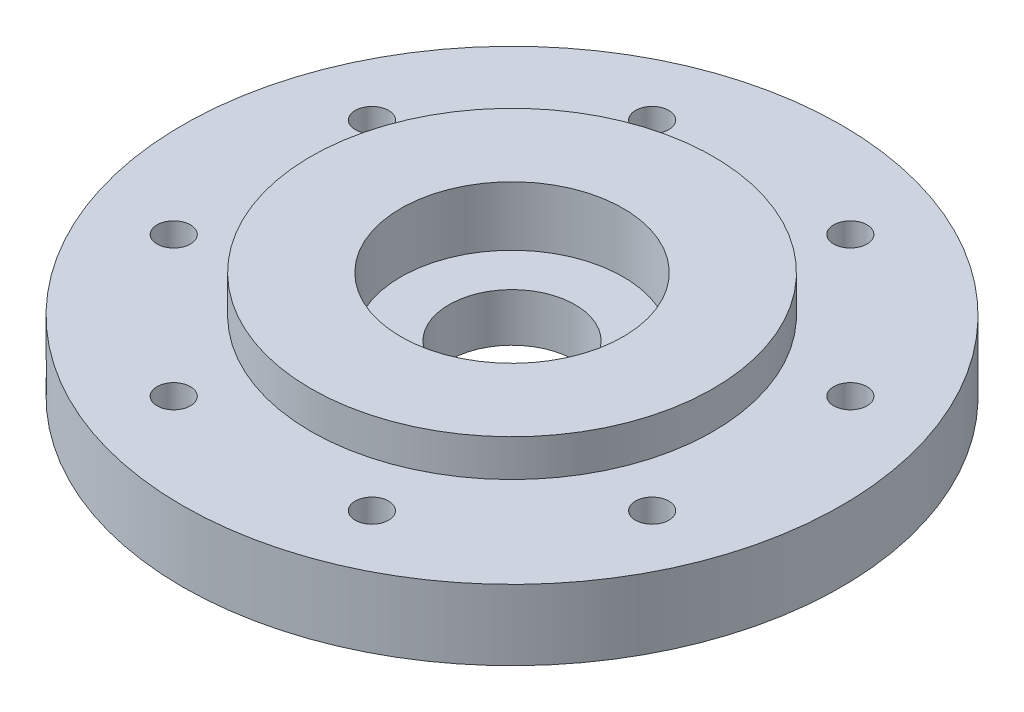
SolidWorks part; units mm, degrees
material "1060 Alloy"
ref_plane "Front" through (0, 0, 0) normal (0, 0, 1) x (1, 0, 0)
ref_plane "Top" through (0, 0, 0) normal (0, 1, 0) x (1, 0, 0)
ref_plane "Right" through (0, 0, 0) normal (1, 0, 0) x (0, 0, -1)
sketch "Sketch1" plane through (0, 0, 0) normal (0, 1, 0) x (1, 0, 0)
  circle A4 centre (0, 0) radius 8.5
  circle A5 centre (0, 0) radius 44.45
  point P0 (0, 0)
  point P17 (0, 0)
  dimension "D6" = 17
  dimension "D1" = 88.9
extrude "body and center hole" add sketch "Sketch1" along normal blind 14.5
sketch "Sketch5" plane through (0, 14.5, 0) normal (0, 1, 0) x (1, 0, 0)
  circle A0 centre (0, 0) radius 15
  dimension "D1" = 30
extrude "big seal cut" cut sketch "Sketch5" against normal blind 8
sketch "Sketch6" plane through (0, 14.5, 0) normal (0, 1, 0) x (1, 0, 0)
  line L0 (0, 0) -> (0, 44.45) construction
  line L1 (0, 0) -> (17.0103, 41.0664) construction
  circle A0 centre (0, 0) radius 44.45 construction
  circle A1 centre (13.3652, 32.2665) radius 2.25
  dimension "D2" = 4.5
  dimension "D1" = 22.5
  dimension "D3" = 34.925
extrude "impeller housing bolt holes" cut sketch "Sketch6" against normal blind 38
pattern_circular "impeller housing bolt pattern" count 8 over 360 about axis through (0, 0, 0) along (0, 1, 0) of "impeller housing bolt holes"
sketch "Sketch7" plane through (0, 14.5, 0) normal (0, 1, 0) x (1, 0, 0)
  circle A0 centre (0, 0) radius 27.1319
  circle A1 centre (0, 0) radius 44.45
  circle A3 centre (0, 0) radius 44.45 construction
  dimension "D1" = 54.2638
extrude "impeller recess" cut sketch "Sketch7" against normal blind 5
sketch "Sketch8" plane through (0, 0, 0) normal (0, -1, 0) x (-1, 0, 0)
  line L0 (0, 0) -> (0, 44.45) construction
  circle A0 centre (0, 0) radius 25.4 construction
  circle A1 centre (0, -25.4) radius 3
  circle A2 centre (0, 0) radius 44.45 construction
  dimension "D1" = 50.8
  dimension "D2" = 6
extrude "bolt hole" cut sketch "Sketch8" against normal blind 7.5 contours A1
pattern_circular "big bolt pattern" count 4 over 360 about axis through (0, 0, 0) along (0, 1, 0) of "bolt hole"
ref_plane "pressure tap orientation" through (-10.5787, 0, 10.5787) normal (-0.7071, 0, 0.7071) x (0.7071, 0, 0.7071)
sketch "Sketch9" plane through (-10.5787, 0, 10.5787) normal (-0.7071, 0, 0.7071) x (0.7071, 0, 0.7071)
  line L0 (0, 6.5) -> (0, 0) construction
  line L1 (15, 6.5) -> (-15, 6.5) construction
  circle A0 centre (0, 3.25) radius 1
  dimension "D1" = 2
extrude "pressure hole" cut sketch "Sketch9" against normal blind 10 and the other way blind 50
sketch "pressure tap end position" plane through (0, 0, 0) normal (0, 1, 0) x (1, 0, 0)
  line L0 (0, 0) -> (-31.4309, -31.4309) construction
  line L1 (-6.6758, -5.2616) -> (-32.13, -30.7158) construction
  circle A0 centre (0, 0) radius 44.45 construction
ref_plane "pressure tap face plane" through (-31.4309, 0, 31.4309) normal (-0.7071, 0, 0.7071) x (0.7071, 0, 0.7071)
sketch "Sketch12" plane through (-31.4309, 0, 31.4309) normal (-0.7071, 0, 0.7071) x (0.7071, 0, 0.7071)
  circle A0 centre (0, 3.25) radius 2.5
  dimension "D1" = 5
extrude "pressure tap fitting bore" cut sketch "Sketch12" against normal blind 8
equation "\"D6@Sketch1\"=\"impeller boss diameter\"+2mm"
equation "\"D1@body and center hole\"=\"big seal plate thickness\""
equation "\"bearing OD\" = 30mm"
equation "\"bearing outer race thickness\"= 1mm"
equation "\"bearing ID\"= 10mm"
equation "\"bearing depth\"= 9mm"
equation "\"bearing inner race thickness\"= 1mm"
equation "\"small seal OD\" = 20mm"
equation "\"small seal ID\"= 8mm"
equation "\"small seal depth\" = 6mm"
equation "\"big seal OD\" = 30mm"
equation "\"big seal ID\"= 15mm"
equation "\"big seal depth\"= 8mm"
equation "\"z\" = 12"
equation "\"de\" = 0.426in"
equation "\"d2\" = 2.097in"
equation "\"d_exit\" =\"b2\""
equation "\"theta\" = 15"
equation "\"b2\" = .15in"
equation "\"b1\" = \"b2\" + (\"d2\"/2 - \"de\"/2)*sin(\"theta\")"
equation "\"s\" = ( 1/\"z\")*(3.14*\"de\" - (3.14*(\"de\"^2) / (4*(\"b1\"))))"
equation "\"s_opening\" = (3.14*\"de\" - \"z\"*\"s\")/\"z\""
equation "\"area_eye\"=3.14*(\"de\"^2)/4"
equation "\"single_channel_area\"=\"s_opening\"*\"b1\""
equation "\"impeller upper clearance\"= .5mm"
equation "\"impeller horizontal clearance\"= .5mm"
equation "\"impeller bottom clearance\"= .5mm"
equation "\"impeller base thickness\"= 2mm"
equation "\"impeller boss depth\" = 14mm"
equation "\"impeller boss diameter\" = \"big seal ID\""
equation "\"impeller dowel diameter\" = 2mm"
equation "\"impeller bolt head diameter\" = 7.5mm"
equation "\"impeller bolt head depth\" = 4mm"
equation "\"impeller shaft bore\"= 8mm"
equation "\"impeller shaft bore depth\" = \"impeller boss depth\" + \"impeller base thickness\" - \"impeller bolt head depth\" - 3mm"
equation "\"impeller dowel length\" = 2mm*2 + \"impeller shaft bore\""
equation "\"impeller screw hole bore\" = 4mm"
equation "\"shaft impeller screw hole diameter\" = \"impeller screw hole bore\""
equation "\"shaft impeller section length\" = \"impeller shaft bore depth\""
equation "\"shaft impeller screw hole depth\" = \"shaft impeller section length\"-\"impeller dowel diameter\"-2mm"
equation "\"shaft impeller section diameter\" = \"impeller shaft bore\""
equation "\"shaft seal section diameter\"=\"small seal ID\""
equation "\"shaft seal section length\"=\"small seal depth\" + 2mm"
equation "\"shaft bearing section diameter\" = \"bearing ID\""
equation "\"shaft bearing section length\" = \"bearing depth\""
equation "\"shaft bearing stop diameter\" = \"bearing ID\" + 2mm"
equation "\"shaft bearing stop length\" = 2mm"
equation "\"shaft coupler section diameter\" = 8mm"
equation "\"shaft coupler section length\" = \"shaft bearing stop length\" + \"coupler length\"/2 + 4mm"
equation "\"coupler motor shaft hole ID\"= 8mm"
equation "\"coupler OD\"= 17mm"
equation "\"coupler length\"= 25mm"
equation "\"square plate diameter\" = 3in"
equation "\"square plate bolt pattern diameter\"= 2in"
equation "\"square plate bolt hole ID\" = 8mm"
equation "\"bearing plate bearing stop ID\" = \"bearing OD\" - 4mm"
equation "\"bearing plate bearing stop depth\" = 3mm"
equation "\"bearing plate thickness\" = \"bearing depth\" + \"bearing plate bearing stop depth\""
equation "\"small seal plate lip depth\" = \"shaft bearing stop length\" + 1mm"
equation "\"small seal plate lip ID\" = \"small seal OD\" - 3mm"
equation "\"small seal plate thickness\" = \"small seal plate lip depth\" + \"small seal depth\""
equation "\"big seal plate lip depth\" = 3mm"
equation "\"big seal plate thickness\" = \"shaft bearing stop length\" + \"shaft seal section length\" + \"impeller boss depth\" - \"impeller bottom clearance\"-\"small seal plate thickness\""
equation "\"motor to housing distance\" = \"motor shaft pride\" + \"shaft coupler section length\" - \"bearing plate bearing stop depth\" + 2mm"
equation "\"motor mount coupler hole diameter\"= \"coupler OD\"+ 4mm"
equation "\"motor mount to housing post radius\"= ( 3 * \"square plate bolt hole ID\" ) / 2"
equation "\"motor mount m4 screw hole diameter\"= 4mm"
equation "\"motor mount m4 head diameter\"= 7.25mm"
equation "\"motor mount m4 head depth\"= 4mm"
equation "\"motor mount plate thickness\"= 8mm + \"motor mount m4 head depth\""
equation "\"impeller cavity center height\"= \"impeller bottom clearance\" + \"impeller upper clearance\" + \"final impeller center height\""
equation "\"impeller cavity diameter\"= 2 * \"impeller horizontal clearance\" + \"d2\""
equation "\"impeller cavity outer height\"= \"impeller bottom clearance\" + \"impeller upper clearance\" + \"impeller base thickness\" + \"b2\""
equation "\"motor shaft pride\"= 32mm"
equation "\"motor shaft flat section length from tip\"= 25.7mm"
equation "\"motor shaft bore end clearance\"= 2mm"
equation "\"coupler shaft to motor clearance\" = 2mm"
equation "\"motor mount shaft hole depth\"= \"motor shaft pride\""
equation "\"impeller housing bolt count\" = 8"
equation "\"impeller housing bolt diameter\" = 6mm"
equation "\"impeller housing bolt pattern diameter\" = 2.75in"
equation "\"impeller housing o-ring channel height\"= 1.5mm"
equation "\"impeller housing o ring channel width\"= 1.5mm"
equation "\"impeller housing o-ring diameter\" = 2in"
equation "\"impeller housing threaded inlet diameter\" = 14mm"
equation "\"impeller housing threaded inlet depth\"= 8mm"
equation "\"impeller housing thickness\"= \"impeller housing threaded inlet depth\" + \"impeller cavity center height\"+ 4mm"
equation "\"impeller housing exit threaded diameter\"= 8mm"
equation "\"impeller housing exit threaded depth\"= 8mm"
equation "\"impeller housing diameter\" = 3.5in"
equation "\"impeller housing diffuser conical angle\"=10"
equation "\"impeller housing diffuser tangent angle\"=20"
equation "\"impeller housing outlet purchase\" = 5mm"
equation "\"D1@Sketch1\"=\"impeller housing diameter\""
equation "\"D1@Sketch5\"=\"big seal OD\""
equation "\"D1@big seal cut\" = \"big seal depth\""
equation "\"D1@Sketch6\"=360 / \"impeller housing bolt count\" / 2"
equation "\"D2@Sketch6\"=\"impeller housing bolt diameter\"-1.5mm"
equation "\"D3@Sketch6\"=\"impeller housing bolt pattern diameter\"/2"
equation "\"D1@Sketch7\"=\"impeller cavity diameter\""
equation "\"D1@impeller recess\" = \"impeller housing outlet purchase\""
equation "\"D1@Sketch8\"=\"square plate bolt pattern diameter\""
equation "\"D2@Sketch8\"=\"square plate bolt hole ID\"-2mm"
equation "\"D1@bolt hole\" = \"big seal plate thickness\" - \"impeller housing outlet purchase\" - 2mm"
equation "\"bit size\" = 2mm"
equation "\"inlet area before cut\" = \"bit size\" * (\"z\") * \"b1\""
equation "\"area to cut\" = \"inlet area before cut\" - \"area_eye\""
equation "\"height to cut\" = \"area to cut\" / ((\"z\")* \"bit size\")"
equation "\"final impeller center height\" = \"impeller base thickness\" + \"b1\" - \"height to cut\""
equation "\"big seal plate pressure hole diameter\" = 2mm"
equation "\"big seal plate pressure tap diameter\" = 5mm"
equation "\"big seal plate pressure tap depth\" = 8mm"
equation "\"motor mount m4 pattern diamater\" = 30mm"
equation "\"D1@Sketch12\"=\"big seal plate pressure tap diameter\""
equation "\"D1@pressure tap fitting bore\" = \"big seal plate pressure tap depth\""
